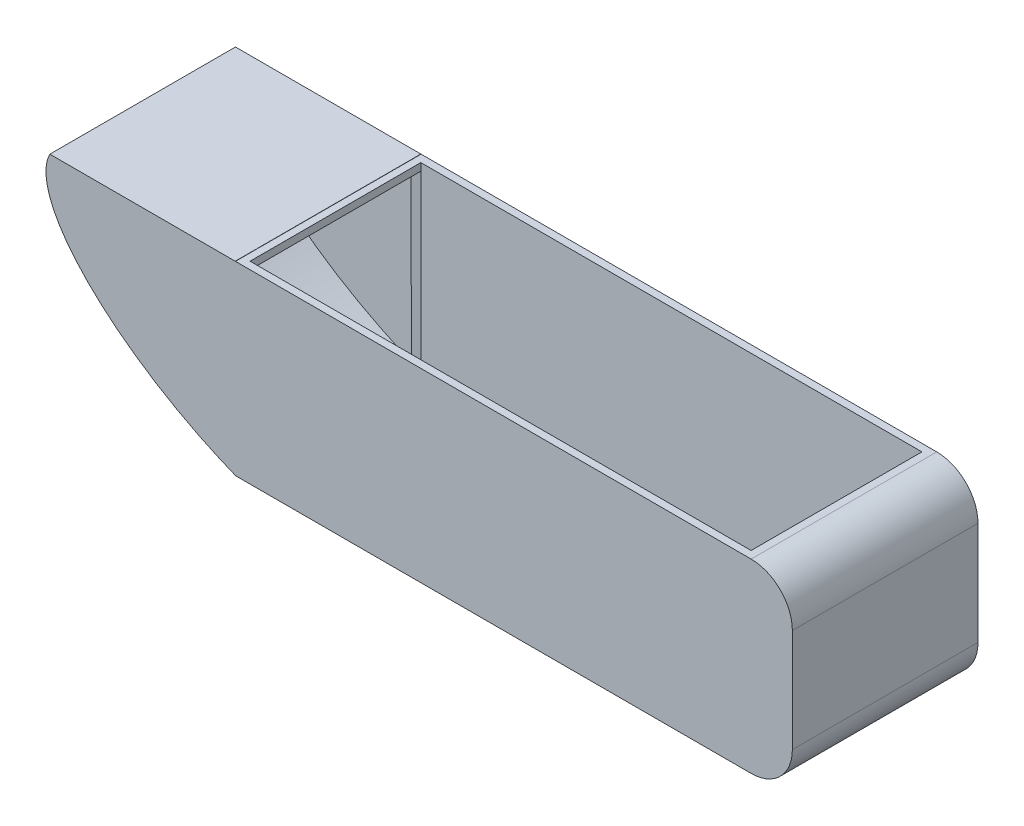
SolidWorks part; units mm, degrees
material "ABS"
ref_plane "Plan de face" through (0, 0, 0) normal (0, 0, 1) x (1, 0, 0)
ref_plane "Plan de dessus" through (0, 0, 0) normal (0, 1, 0) x (1, 0, 0)
ref_plane "Plan de droite" through (0, 0, 0) normal (1, 0, 0) x (0, 0, -1)
sketch "Esquisse1" plane through (0, 0, 0) normal (0, 0, 1) x (1, 0, 0)
  line L0 (0, 250) -> (-250, 250) construction
  line L1 (0, 0) -> (694.4613, 0)
  line L2 (0, 0) -> (0, 0.1339)
  line L3 (0, 250) -> (694.4613, 250)
  line L4 (750, 55.5387) -> (750, 194.4613)
  line L5 (0, 0) -> (-250, 0)
  line L6 (-250, 250) -> (-0.3348, 250)
  line L7 (0, 249.8661) -> (0, 250)
  arc A0 (694.4613, 250) -> (750, 194.4613) centre (694.4613, 194.4613) cw
  arc A1 (694.4613, 0) -> (750, 55.5387) centre (694.4613, 55.5387) ccw
  ellipse E0 centre (0, 125) end of major axis (-250, 250) minor radius 113.9816 (-250, 250) -> (0.3348, 0) ccw
  ellipse E1 centre (0, 125) end of major axis (-250, 250) minor radius 113.9816 (0, 249.8661) -> (-0.3348, 250) ccw
  point P22 (750, 250)
  dimension "D4" = 55.5387
  dimension "D5" = 55.5387
  dimension "D1" = 750
  dimension "D2" = 250
  dimension "D3" = 250
extrude "Boss.-Extru.1" add sketch "Esquisse1" along normal blind 250 contours L7 E1 L6 E0 L1 A1 L4 A0 L3
sketch "Esquisse2" plane through (0, 250, 0) normal (0, 1, 0) x (1, 0, 0)
  line L0 (0, 0) -> (694.4613, 0) construction
  line L1 (9.6652, -10) -> (684.4613, -10)
  line L2 (9.6652, -10) -> (9.6652, -240)
  line L3 (9.6652, -240) -> (684.4613, -240)
  line L4 (684.4613, -10) -> (684.4613, -240)
  line L5 (-0.3348, -250) -> (-0.3348, 0) construction
  line L6 (0, -250) -> (694.4613, -250) construction
  line L7 (694.4613, -250) -> (694.4613, 0) construction
  dimension "D1" = 10
  dimension "D2" = 10
  dimension "D3" = 10
  dimension "D4" = 10
extrude "Enlèv. mat.-Extru.1" cut sketch "Esquisse2" against normal blind 240
sketch "Esquisse3" plane through (684.4613, 0, 0) normal (-1, 0, 0) x (0, 0, 1)
  line L0 (250, 250) -> (0, 250) construction
  line L1 (10, 240) -> (240, 240)
  line L2 (10, 240) -> (10, 10)
  line L3 (10, 10) -> (240, 10)
  line L4 (240, 240) -> (240, 10)
  line L5 (250, 0) -> (250, 250) construction
  line L6 (250, 0) -> (0, 0) construction
  dimension "D1" = 10
  dimension "D2" = 10
  dimension "D3" = 10
  dimension "D4" = 10
extrude "Enlèv. mat.-Extru.2" cut sketch "Esquisse3" against normal blind 40 draft 66
sketch "Esquisse5" plane through (0, 0, 250) normal (0, 0, 1) x (1, 0, 0)
  line L0 (0.3217, 9.7982) -> (0.0134, 240) construction
  line L4 (0.0134, 240) -> (0.3217, 9.7982)
  line L5 (0.0134, 240) -> (-243.5781, 240)
  ellipse E0 centre (0.1675, 124.8991) end of major axis (-241.2969, 245.5505) minor radius 104.8262 (-243.5781, 240) -> (0.3217, 9.7982) ccw
  point P4 (0.3214, 10)
  point P7 (-241.2969, 245.5505)
  point P10 (0.0134, 240)
  point P15 (-243.2821, 241.1604)
  point P18 (-244.9345, 238.5868)
  point P20 (-2.3164, 9.2661)
  point P21 (3.0525, 11.3262)
  point P23 (-3.1748, 243.1356)
  point P24 (3.4857, 237.4997)
  point P25 (4.0621, 242.303)
  dimension "D5" = 3.1356
  dimension "D6" = 1.1604
  dimension "D7" = 270.1849
  dimension "D8" = 269.7859
  dimension "D9" = 115.6597
  dimension "D10" = 113.5729
extrude "Enlèv. mat.-Extru.6" cut sketch "Esquisse5" against normal blind 230 from offset 10 offset against normal yes
sketch "Esquisse7" plane through (9.6652, 0, 0) normal (1, 0, 0) x (0, 0, -1)
  line L0 (-250, 0) -> (0, 0) construction
  line L1 (-10, 10) -> (-240, 10)
  line L2 (-10, 10) -> (-10, 240)
  line L3 (-10, 240) -> (-240, 240)
  line L4 (-240, 10) -> (-240, 240)
  line L5 (-250, 55.5387) -> (-250, 194.4613) construction
  line L6 (0, 55.5387) -> (0, 194.4613) construction
  line L7 (-250, 250) -> (0, 250) construction
  dimension "D1" = 10
  dimension "D2" = 10
  dimension "D3" = 10
  dimension "D4" = 10
extrude "Enlèv. mat.-Extru.7" cut sketch "Esquisse7" against normal blind 20 draft 20
